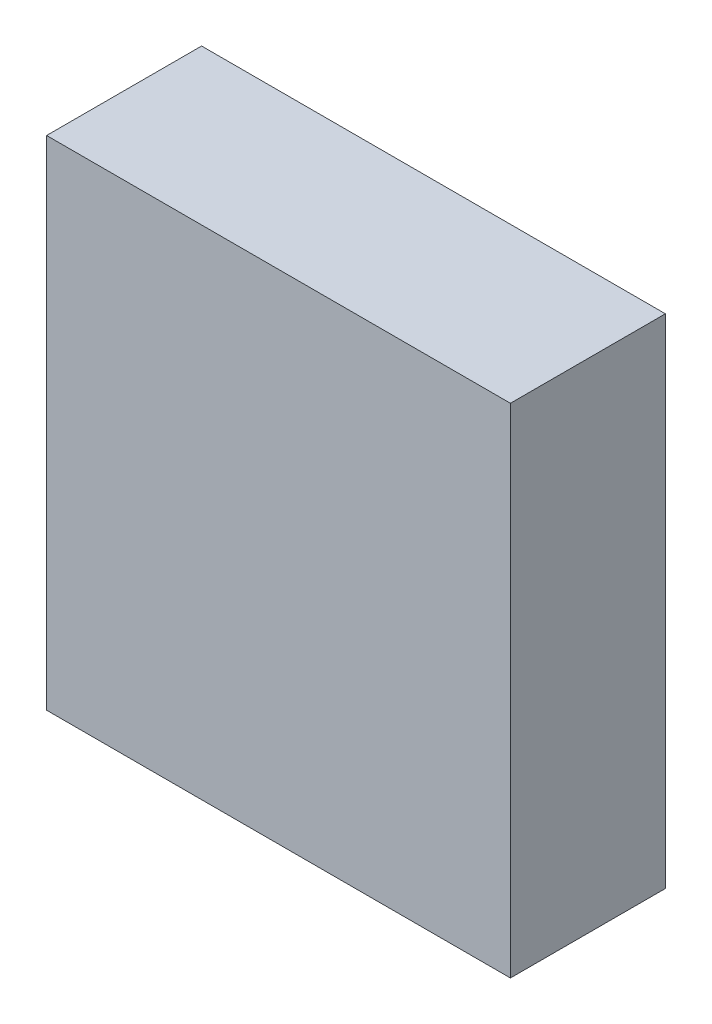
SolidWorks part; units mm, degrees
ref_plane "Front Plane" through (0, 0, 0) normal (0, 0, 1) x (1, 0, 0)
ref_plane "Top Plane" through (0, 0, 0) normal (0, 1, 0) x (1, 0, 0)
ref_plane "Right Plane" through (0, 0, 0) normal (1, 0, 0) x (0, 0, -1)
sketch "Sketch1" plane through (0, 0, 0) normal (0, 0, 1) x (1, 0, 0)
  line L1 (-102.5, 110) -> (102.5, 110)
  line L2 (-102.5, 110) -> (-102.5, -110)
  line L3 (-102.5, -110) -> (102.5, -110)
  line L4 (102.5, 110) -> (102.5, -110)
  line L5 (-102.5, 110) -> (102.5, -110) construction
  line L6 (-102.5, -110) -> (102.5, 110) construction
  point P0 (0, 0)
  dimension "D1" = 220
  dimension "D2" = 205
extrude "Boss-Extrude1" add sketch "Sketch1" along normal blind 68.5
